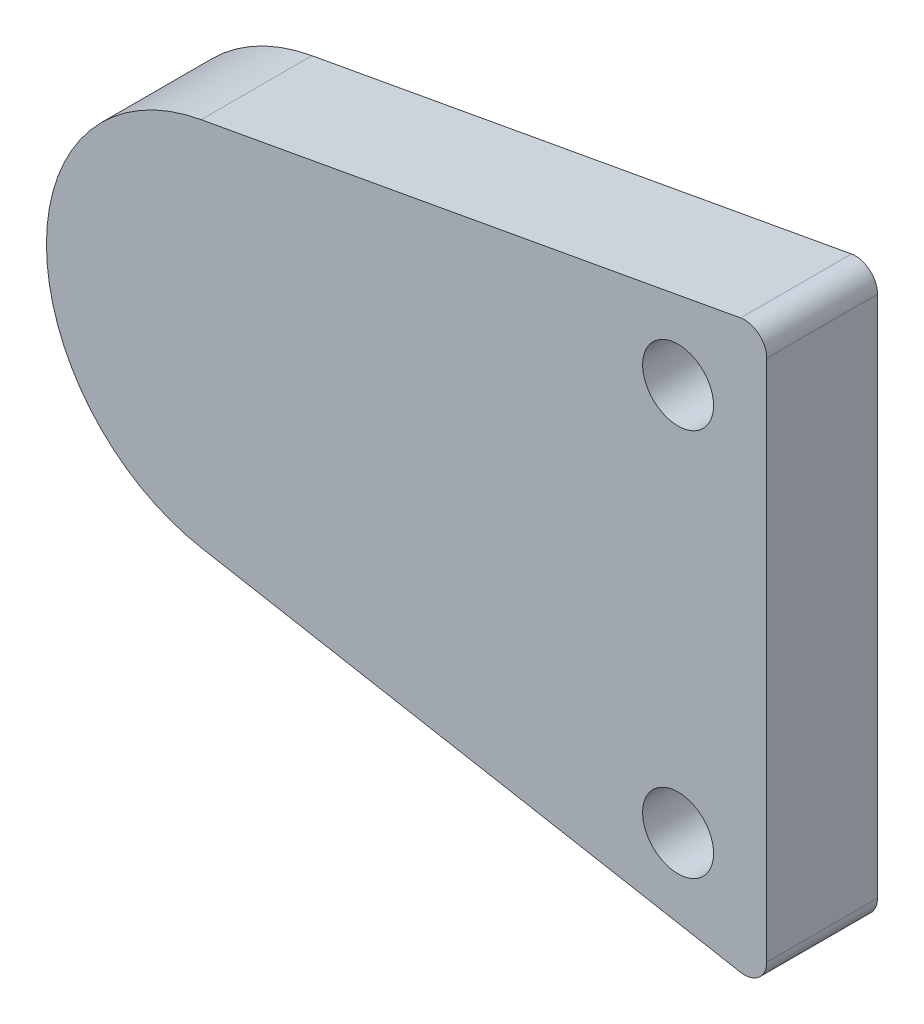
SolidWorks part; units mm, degrees
ref_plane "前视基准面" through (0, 0, 0) normal (0, 0, 1) x (1, 0, 0)
ref_plane "上视基准面" through (0, 0, 0) normal (0, 1, 0) x (1, 0, 0)
ref_plane "右视基准面" through (0, 0, 0) normal (1, 0, 0) x (0, 0, -1)
other "Configuration Table"
sketch "草图1" plane through (0, 0, 0) normal (0, 0, 1) x (1, 0, 0)
  line L3 (1.7389, 8.75) -> (20, 8.75) construction
  line L4 (-1.5196, 8.3631) -> (22.8212, 12.7858)
  line L5 (24, 11.8019) -> (24, -11.8019)
  line L6 (22.8212, -12.7858) -> (-1.5196, -8.3631)
  line L7 (0, 0) -> (-5.0535, 0) construction
  arc A0 (-1.5196, 8.3631) -> (-1.5196, -8.3631) centre (0, 0) ccw
  circle A1 centre (20, 8.75) radius 1.6
  circle A2 centre (20, -8.75) radius 1.6
  arc A3 (24, 11.8019) -> (22.8212, 12.7858) centre (23, 11.8019) ccw
  arc A4 (24, -11.8019) -> (22.8212, -12.7858) centre (23, -11.8019) cw
  circle A5 centre (0, 0) radius 5.5
  point P16 (24, 13)
  point P19 (24, -13)
  dimension "D1" = 17
  dimension "D4" = 3.2
  dimension "D5" = 26
  dimension "D7" = 1
  dimension "D8" = 1
  dimension "D9" = 11
  dimension "D2" = 8.75
  dimension "D3" = 20
  dimension "D6" = 24
extrude "凸台-拉伸2" add sketch "草图1" along normal blind 2.5
sketch "草图2" plane through (0, 0, 2.5) normal (0, 0, 1) x (1, 0, 0)
  line L3 (-1.5196, -8.3631) -> (22.8212, -12.7858)
  line L4 (24, -11.8019) -> (24, 11.8019)
  line L5 (22.8212, 12.7858) -> (-1.5196, 8.3631)
  line L6 (-1.5196, -8.3631) -> (22.8212, -12.7858)
  line L7 (24, -11.8019) -> (24, 11.8019)
  line L8 (22.8212, 12.7858) -> (-1.5196, 8.3631)
  circle A0 centre (20, -8.75) radius 1.6 construction
  circle A1 centre (20, -8.75) radius 1.6
  circle A2 centre (20, 8.75) radius 1.6 construction
  arc A3 (-1.5196, 8.3631) -> (-1.5196, -8.3631) centre (0, 0) ccw
  arc A4 (22.8212, -12.7858) -> (24, -11.8019) centre (23, -11.8019) ccw
  arc A5 (24, 11.8019) -> (22.8212, 12.7858) centre (23, 11.8019) ccw
  arc A6 (-1.5196, 8.3631) -> (-1.5196, -8.3631) centre (0, 0) ccw
  arc A7 (22.8212, -12.7858) -> (24, -11.8019) centre (23, -11.8019) ccw
  arc A8 (24, 11.8019) -> (22.8212, 12.7858) centre (23, 11.8019) ccw
  circle A9 centre (20, 8.75) radius 1.6
  dimension "D1" = 0
extrude "凸台-拉伸3" add sketch "草图2" along normal blind 2.5
